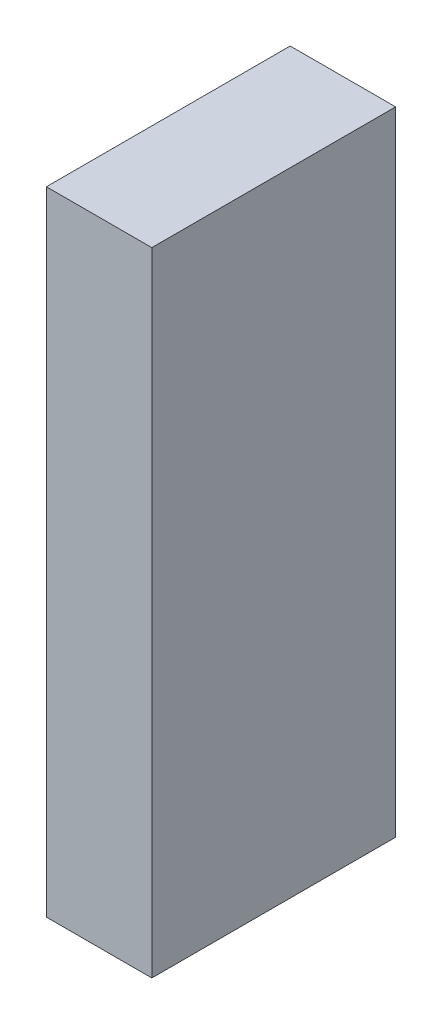
SolidWorks part; units mm, degrees
material "Pine"
ref_plane "Front Plane" through (0, 0, 0) normal (0, 0, 1) x (1, 0, 0)
ref_plane "Top Plane" through (0, 0, 0) normal (0, 1, 0) x (1, 0, 0)
ref_plane "Right Plane" through (0, 0, 0) normal (1, 0, 0) x (0, 0, -1)
sketch "Sketch1" plane through (0, 0, 0) normal (0, 1, 0) x (1, 0, 0)
  line L1 (19.05, -44.0531) -> (-19.05, -44.0531)
  line L2 (19.05, -44.0531) -> (19.05, 44.0531)
  line L3 (19.05, 44.0531) -> (-19.05, 44.0531)
  line L4 (-19.05, -44.0531) -> (-19.05, 44.0531)
  line L5 (19.05, -44.0531) -> (-19.05, 44.0531) construction
  line L6 (19.05, 44.0531) -> (-19.05, -44.0531) construction
  point P0 (0, 0)
  dimension "D1" = 38.1
  dimension "D2" = 88.1063
extrude "Boss-Extrude1" add sketch "Sketch1" along normal blind 228.6
